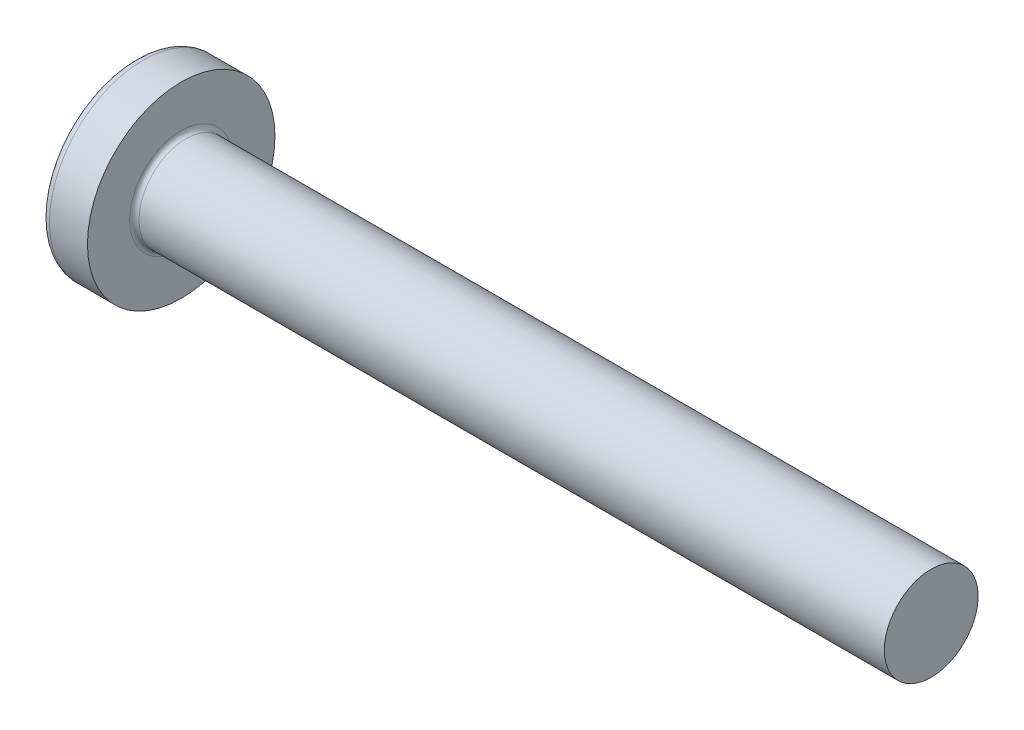
SolidWorks part; units mm, degrees
ref_plane "Plane1" through (0, 0, 0) normal (0, 0, 1) x (1, 0, 0)
ref_plane "Plane2" through (0, 0, 0) normal (0, 1, 0) x (1, 0, 0)
ref_plane "Plane3" through (0, 0, 0) normal (1, 0, 0) x (0, 0, -1)
sketch "BodySke" plane through (0, 0, 0) normal (0, 0, 1) x (1, 0, 0)
  line L0 (1.6, 1) -> (1.6, 2)
  line L1 (1.8, 6.35) -> (1.8, -3.175) construction
  line L2 (-25.4, 0) -> (127, 0) construction
  line L3 (17.6, 0) -> (0, 0)
  line L4 (1.6, 1) -> (17.6, 1)
  line L5 (17.6, 1) -> (17.6, 0)
  line L6 (0.79, 2) -> (1.6, 2)
  line L8 (1.6, 6.35) -> (1.6, -3.175) construction
  arc A0 (0.6464, 1.9285) -> (0, 0) centre (3.2, 0) ccw
  arc A2 (0.6464, 1.9285) -> (0.79, 2) centre (0.79, 1.82) cw
  dimension "Head_crown_rad" = 3.2
  dimension "Head_fillet_rad" = 0.18
  dimension "Length" = 16
  dimension "Head_ht" = 1.6
  dimension "Head_dia" = 4
  dimension "Advance" = 0.4
  dimension "Thread_nom" = 16
  dimension "Diameter" = 2
revolve "Base-Revolve" add sketch "BodySke"
cosmetic thread "ThreadCosmetic" [suppressed]
fillet "Fillet1" radius 0.1 1 edges at (1.6, 0, 1)
sketch "Sketch3" plane through (0, 0, 0) normal (1, 0, 0) x (0, 0, -1)
  line L0 (0.24, -1.05) -> (-0.24, -1.05)
  line L1 (0.24, -1.05) -> (0.24, 1.05)
  line L2 (-0.24, 1.05) -> (0.24, 1.05)
  line L3 (-0.24, 1.05) -> (-0.24, -1.05)
  dimension "Cross_dia" = 2.1
  dimension "D1" = 1.05
  dimension "Cross_width" = 0.48
  dimension "D2" = 0.24
ref_plane "Plane4" through (1.42, 0, 0) normal (1, 0, 0) x (0, 0, -1)
sketch "Sketch4" plane through (1.42, 0, 0) normal (1, 0, 0) x (0, 0, -1)
  line L0 (0.24, -0.342) -> (-0.24, -0.342)
  line L1 (0.24, -0.342) -> (0.24, 0.342)
  line L2 (-0.24, 0.342) -> (0.24, 0.342)
  line L3 (-0.24, 0.342) -> (-0.24, -0.342)
  dimension "D1" = 0.48
  dimension "D2" = 0.684
  dimension "D3" = 0.24
  dimension "D4" = 0.342
loft "Recess" cut profiles "Sketch3", "Sketch4"
pattern_circular "RecPat" count 2 every 90 about axis through (0, 0, 0) along (1, 0, 0) of "Recess"
sketch "RecCorSke" plane through (0, 0, 0) normal (0, 0, 1) x (1, 0, 0)
  line L0 (-3.175, 0) -> (15.875, 0) construction
  line L1 (-25.4, 0) -> (127, 0) construction
  line L2 (0, 0) -> (0, 0.4548)
  line L3 (0, 0.4548) -> (1.42, 0.3555)
  line L4 (1.42, 0.3555) -> (1.5355, 0)
  line L5 (1.5355, 0) -> (0, 0)
  dimension "Diameter" = 0.711
  dimension "Depth" = 1.42
  dimension "Draft_angle" = 4
  dimension "Bottom_angle" = 18
revolve "RecessCore" cut sketch "RecCorSke" angle 360 about L0
sketch "ThdSchSke" plane through (0, 0, 0) normal (0, 0, 1) x (1, 0, 0)
  line L0 (2.4, -0.774) -> (2.2418, -1)
  line L1 (2.4, -0.774) -> (2.5582, -1)
  line L2 (2.5582, -1) -> (2.5582, -1.25)
  line L3 (-3.175, 0) -> (5.1513, 0) construction
  line L5 (2.5582, -1.25) -> (2.2418, -1.25)
  line L6 (2.2418, -1.25) -> (2.2418, -1)
  dimension "Diameter" = 2
  dimension "SideAngle" = 55
  dimension "VeeAngle" = 70
  dimension "Thread_minor" = 1.548
  dimension "Overcut" = 2.5
  dimension "Start" = 2.4
revolve "ThreadSchematic" [suppressed] cut sketch "ThdSchSke" angle 360 about L3
pattern_linear "ThdSchPat" [suppressed]
equation "\"D1@Sketch3\" = \"Cross_dia@Sketch3\" / 2"
equation "\"D2@Sketch3\" = \"Cross_width@Sketch3\" / 2"
equation "\"Depth@RecCorSke\" = \"Cross_depth@Plane4\""
equation "\"D1@Sketch4\" = \"Cross_width@Sketch3\""
equation "\"D2@Sketch4\" = \"Cross_dia@Sketch3\" - 2.0 * \"Cross_depth@Plane4\" * tan(26.5  * 0.017453292)"
equation "\"D3@Sketch4\" = \"D1@Sketch4\" / 2"
equation "\"D4@Sketch4\" = \"D2@Sketch4\" / 2"
equation "\"Thread_length@ThreadCosmetic\" = ((sgn( (\"Length@BodySke\" - \"Advance@BodySke\" * 2.0 ) - \"Thread_nom@BodySke\" )-1)*( (\"Length@BodySke\" - \"Advance@BodySke\" * 2.0 ) - \"Thread_nom@BodySke\" ))/-2+ \"Thread_nom@BodySke\""
equation "\"Thread_minor@ThdSchSke\" = \"Thread_minor@ThreadCosmetic\""
equation "\"Diameter@ThdSchSke\" = \"Diameter@BodySke\""
equation "\"Overcut@ThdSchSke\" = \"Diameter@BodySke\" * 1.25"
equation "\"Start@ThdSchSke\" = \"Head_ht@BodySke\" + \"Length@BodySke\" - \"Thread_length@ThreadCosmetic\"  '---Non-countersunk---"
equation "\"Num_threads@ThdSchPat\" = int( \"Thread_length@ThreadCosmetic\" / \"Advance@BodySke\" + 0.999 )  + 1"
equation "\"Advance@ThdSchPat\" = \"Thread_length@ThreadCosmetic\" /  (\"Num_threads@ThdSchPat\" - 1) 'relax it"
